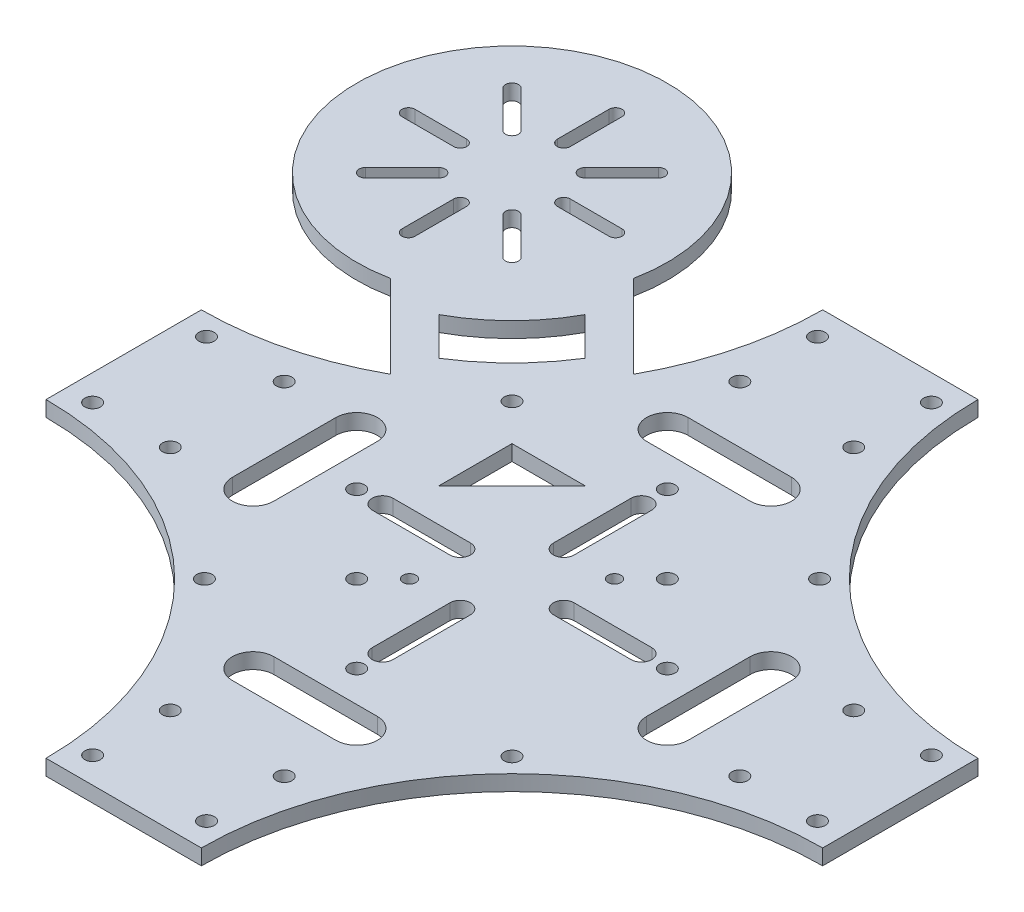
SolidWorks part; units mm, degrees
ref_plane "前视基准面" through (0, 0, 0) normal (0, 0, 1) x (1, 0, 0)
ref_plane "上视基准面" through (0, 0, 0) normal (0, 1, 0) x (1, 0, 0)
ref_plane "右视基准面" through (0, 0, 0) normal (1, 0, 0) x (0, 0, -1)
sketch "草图1" plane through (0, 0, 0) normal (0, 1, 0) x (1, 0, 0)
  line L0 (0, 0) -> (0, 75)
  line L1 (0, 0) -> (75, 0)
  line L2 (0, 0) -> (0, -75)
  line L3 (0, 0) -> (-75, 0)
  line L4 (0, 75) -> (15, 75)
  line L5 (0, 75) -> (-15, 75)
  line L6 (75, 0) -> (75, 15)
  line L7 (75, 0) -> (75, -15)
  line L8 (0, -75) -> (15, -75)
  line L9 (0, -75) -> (-15, -75)
  line L10 (-75, 0) -> (-75, -15)
  line L11 (-75, 0) -> (-75, 15)
  line L12 (75, 0) -> (70, 0)
  arc A0 (-75, 15) -> (-15, 75) centre (-75, 75) ccw
  arc A1 (15, 75) -> (75, 15) centre (75, 75) ccw
  arc A2 (75, -15) -> (15, -75) centre (75, -75) ccw
  arc A3 (-15, -75) -> (-75, -15) centre (-75, -75) ccw
  circle A4 centre (-11, 70) radius 1.25
  circle A5 centre (11, 70) radius 1.25
  circle A6 centre (70, -11) radius 1.25
  circle A7 centre (70, 11) radius 1.25
  circle A8 centre (-11, -70) radius 1.25
  circle A9 centre (11, -70) radius 1.25
  circle A10 centre (-70, 11) radius 1.25
  circle A11 centre (-70, -11) radius 1.25
  point P9 (0, 0)
  point P21 (0, 0)
  point P32 (0, 0)
  point P35 (0, 0)
  point P44 (0, 0)
  dimension "D1" = 4
extrude "凸台-拉伸1" add sketch "草图1" along normal blind 3 contours A2 L7 L1 L2 L8 A9 A6 | A3 L9 L2 L3 L10 A11 A8 | A0 L11 L3 L0 L5 A4 A10 | A1 L4 L0 L1 L6 A7 A5
sketch "草图2" plane through (0, 0, 0) normal (0, -1, 0) x (1, 0, 0)
  line L0 (0, 0) -> (-32.5736, -32.5736)
  line L1 (0, 0) -> (32.5736, -32.5736)
  line L2 (-31.4663, 0.3536) -> (-0.3536, 31.4663)
  line L3 (31.4663, -0.3536) -> (-0.3536, 31.4663)
  line L4 (0.3536, -31.4663) -> (31.4663, -0.3536)
  line L5 (0.3536, -31.4663) -> (-31.4663, 0.3536)
  arc A0 (-15, -75) -> (-75, -15) centre (-75, -75) ccw construction
  circle A2 centre (0.3536, -31.4663) radius 1.5
  circle A3 centre (31.4663, -0.3536) radius 1.5
  circle A4 centre (-0.3536, 31.4663) radius 1.5
  circle A5 centre (-31.4663, 0.3536) radius 1.5
  point P12 (-15.5563, -15.5563)
  point P16 (-15.9099, 15.9099)
  point P17 (15.9099, -15.9099)
extrude "切除-拉伸1" cut sketch "草图2" against normal blind 3 contours A3 | A2 | A5 | A4
sketch "草图3" plane through (0, 3, 0) normal (0, 1, 0) x (1, 0, 0)
  line L0 (0.3536, 31.4663) -> (-31.4663, -0.3536)
  line L1 (-15.5563, 15.5563) -> (-22.6274, 22.6274)
  line L2 (-15.5563, 15.5563) -> (-12.0208, 19.0919)
  line L3 (-15.5563, 15.5563) -> (-19.0919, 12.0208)
  line L4 (-19.0919, 12.0208) -> (-22.6274, 22.6274)
  line L5 (-12.0208, 19.0919) -> (-22.6274, 22.6274)
extrude "切除-拉伸2" cut sketch "草图3" against normal blind 3 contours L0 L5 L1 | L4 L0 L1
sketch "草图4" plane through (0, 3, 0) normal (0, 1, 0) x (1, 0, 0)
  line L0 (31.4663, 0.3536) -> (-0.3536, -31.4663)
  line L1 (0, 0) -> (21.2132, -21.2132)
  line L2 (28.2843, -14.1421) -> (14.1421, -28.2843)
  line L3 (14.1421, -28.2843) -> (28.2843, -14.1421) construction
  line L4 (8.4817, -22.6239) -> (22.6239, -8.4817)
  line L5 (19.8025, -33.9447) -> (33.9447, -19.8025)
  arc A0 (8.4817, -22.6239) -> (19.8025, -33.9447) centre (14.1421, -28.2843) ccw
  arc A1 (33.9447, -19.8025) -> (22.6239, -8.4817) centre (28.2843, -14.1421) ccw
  point P9 (21.2132, -21.2132)
extrude "切除-拉伸3" cut sketch "草图4" against normal blind 3
sketch "草图5" plane through (0, 3, 0) normal (0, 1, 0) x (1, 0, 0)
  line L0 (-12.0208, 19.0919) -> (-8.4853, 22.6274)
  line L1 (-8.4853, 22.6274) -> (-22.6274, 22.6274)
  line L2 (-19.0919, 12.0208) -> (-22.6274, 8.4853)
  line L3 (-22.6274, 8.4853) -> (-22.6274, 22.6274)
  line L4 (-12.0208, 19.0919) -> (-22.6274, 22.6274)
  line M28 (-19.0919, 12.0208) -> (-22.6274, 22.6274)
extrude "切除-拉伸4" cut sketch "草图5" against normal blind 10 contours L3 L2 M28 | L4 L0 L1
sketch "草图6" plane through (0, 3, 0) normal (0, 1, 0) x (1, 0, 0)
  line L0 (0, 0) -> (-28.2843, -28.2843)
  line L1 (-28.2843, -28.2843) -> (-35.3553, -21.2132)
  line L2 (0, 0) -> (-22.6274, 22.6274)
  circle A0 centre (-35.3553, -21.2132) radius 1.5
  circle A1 centre (-21.2132, -35.3553) radius 1.5
  circle A2 centre (35.3553, 21.2132) radius 1.5
  circle A3 centre (21.2132, 35.3553) radius 1.5
extrude "切除-拉伸5" cut sketch "草图6" against normal blind 10 contours A1 | A0 | A2 | A3
sketch "草图7" plane through (0, 3, 0) normal (0, 1, 0) x (1, 0, 0)
  circle A0 centre (-29.6985, 29.6985) radius 1.5
  circle A1 centre (29.6985, 29.6985) radius 1.5
  circle A2 centre (29.6985, -29.6985) radius 1.5
  circle A3 centre (-29.6985, -29.6985) radius 1.5
  point P11 (0, 0)
  dimension "D1" = 4
extrude "切除-拉伸8" cut sketch "草图7" against normal blind 10
sketch "草图8" plane through (0, 3, 0) normal (0, 1, 0) x (1, 0, 0)
  circle A0 centre (-11, 55) radius 1.5
  circle A1 centre (11, 55) radius 1.5
  circle A2 centre (55, 11) radius 1.5
  circle A3 centre (55, -11) radius 1.5
  circle A4 centre (11, -55) radius 1.5
  circle A5 centre (-11, -55) radius 1.5
  circle A6 centre (-55, -11) radius 1.5
  circle A7 centre (-55, 11) radius 1.5
  point P21 (0, 0)
  dimension "D1" = 4
extrude "切除-拉伸9" cut sketch "草图8" against normal blind 10
sketch "草图9" plane through (0, 3, 0) normal (0, 1, 0) x (1, 0, 0)
  circle A0 centre (0, 0) radius 15
extrude "切除-拉伸10" cut sketch "草图9" against normal blind 10
sketch "草图11" plane through (0, 3, 0) normal (0, 1, 0) x (1, 0, 0)
  circle A0 centre (-35.3553, -21.2132) radius 1.5
  circle A2 centre (35.3553, 21.2132) radius 1.5
  circle A3 centre (21.2132, 35.3553) radius 1.5
  circle A4 centre (0.3536, 31.4663) radius 1.5
  circle A5 centre (31.4663, 0.3536) radius 1.5
  circle A6 centre (-0.3536, -31.4663) radius 1.5
  circle A7 centre (-31.4663, -0.3536) radius 1.5
  circle A8 centre (-21.2132, -35.3553) radius 1.5
extrude "凸台-拉伸3" add sketch "草图11" against normal blind 3
sketch "草图12" plane through (0, 3, 0) normal (0, 1, 0) x (1, 0, 0)
  line L0 (0, 0) -> (-40, 0)
  line L1 (-40, 0) -> (-40, 10)
  line L2 (-40, 0) -> (-40, -10)
  line L3 (-40, -10) -> (-40, 10) construction
  line L4 (-44, -10) -> (-44, 10)
  line L5 (-36, -10) -> (-36, 10)
  line L6 (-10, 40) -> (10, 40) construction
  line L7 (-10, 44) -> (10, 44)
  line L8 (-10, 36) -> (10, 36)
  line L9 (40, 10) -> (40, -10) construction
  line L10 (44, 10) -> (44, -10)
  line L11 (36, 10) -> (36, -10)
  line L12 (10, -40) -> (-10, -40) construction
  line L13 (10, -44) -> (-10, -44)
  line L14 (10, -36) -> (-10, -36)
  arc A0 (-44, -10) -> (-36, -10) centre (-40, -10) ccw
  arc A1 (-36, 10) -> (-44, 10) centre (-40, 10) ccw
  arc A2 (-10, 44) -> (-10, 36) centre (-10, 40) ccw
  arc A3 (10, 36) -> (10, 44) centre (10, 40) ccw
  arc A4 (44, 10) -> (36, 10) centre (40, 10) ccw
  arc A5 (36, -10) -> (44, -10) centre (40, -10) ccw
  arc A6 (10, -44) -> (10, -36) centre (10, -40) ccw
  arc A7 (-10, -36) -> (-10, -44) centre (-10, -40) ccw
  point P3 (-40, 0)
  point P13 (0, 40)
  point P20 (40, 0)
  point P27 (0, -40)
  point P34 (0, 0)
  dimension "D1" = 4
extrude "切除-拉伸12" cut sketch "草图12" against normal blind 3
sketch "草图14" plane through (0, 3, 0) normal (0, 1, 0) x (1, 0, 0)
  line L0 (22.8277, -8.285) -> (8.285, -22.8277) construction
  line L1 (19.8025, -33.9447) -> (33.9447, -19.8025) construction
  line L2 (8.285, -22.8277) -> (22.8277, -8.285)
  line L3 (22.8277, -8.285) -> (19.8025, -33.9447)
  line L4 (19.8025, -33.9447) -> (33.9447, -19.8025)
  arc A0 (8.285, -22.8277) -> (19.8025, -33.9447) centre (14.1421, -28.2843) ccw
  arc A1 (8.285, -22.8277) -> (19.8025, -33.9447) centre (14.1421, -28.2843) ccw construction
  arc A2 (33.9447, -19.8025) -> (22.8277, -8.285) centre (28.2843, -14.1421) ccw construction
  arc A3 (22.8277, -8.285) -> (32.1857, -7.1522) centre (28.2843, -14.1421) ccw
  circle A4 centre (28.2843, -14.1421) radius 8.005
extrude "凸台-拉伸4" add sketch "草图14" against normal blind 3 contours A3 A4 L3 | L2 A3 L3 | A3 L2 A0 L3 | A3 L3 L4
sketch "草图15" plane through (0, 3, 0) normal (0, 1, 0) x (1, 0, 0)
  circle A0 centre (0, 0) radius 15
extrude "凸台-拉伸5" add sketch "草图15" against normal blind 3
sketch "草图17" plane through (0, 3, 0) normal (0, 1, 0) x (1, 0, 0)
  line L0 (0, 0) -> (0, -20)
  line L1 (0, -20) -> (0, -10) construction
  line L2 (-2, -20) -> (-2, -10)
  line L3 (2, -20) -> (2, -10)
  line L4 (-20, 0) -> (-10, 0) construction
  line L5 (-20, 2) -> (-10, 2)
  line L6 (-20, -2) -> (-10, -2)
  line L7 (0, 20) -> (0, 10) construction
  line L8 (2, 20) -> (2, 10)
  line L9 (-2, 20) -> (-2, 10)
  line L10 (20, 0) -> (10, 0) construction
  line L11 (20, -2) -> (10, -2)
  line L12 (20, 2) -> (10, 2)
  arc A0 (-2, -20) -> (2, -20) centre (0, -20) ccw
  arc A1 (2, -10) -> (-2, -10) centre (0, -10) ccw
  arc A2 (-20, 2) -> (-20, -2) centre (-20, 0) ccw
  arc A3 (-10, -2) -> (-10, 2) centre (-10, 0) ccw
  arc A4 (2, 20) -> (-2, 20) centre (0, 20) ccw
  arc A5 (-2, 10) -> (2, 10) centre (0, 10) ccw
  arc A6 (20, -2) -> (20, 2) centre (20, 0) ccw
  arc A7 (10, 2) -> (10, -2) centre (10, 0) ccw
  point P3 (0, -15)
  point P13 (-15, 0)
  point P20 (0, 15)
  point P27 (15, 0)
  point P33 (0, 0)
  dimension "D1" = 4
extrude "切除-拉伸13" cut sketch "草图17" against normal blind 3 contours L8 A5 L9 A4 | L12 A7 L11 A6 | L3 A1 L2 A0 | L5 A3 L6 A2
sketch "草图18" plane through (0, 3, 0) normal (0, 1, 0) x (1, 0, 0)
  line L0 (0, 0) -> (-32.5736, 32.5736)
  line L1 (-32.5736, 32.5736) -> (-46.7157, 46.7157)
  line L2 (-50.2513, 50.2513) -> (-61.9773, 38.5252)
  line L3 (-46.7157, 46.7157) -> (-50.2513, 50.2513)
  line L4 (-61.9773, 38.5252) -> (-38.5252, 61.9773)
  line L5 (-38.5252, 61.9773) -> (-22.5002, 45.9523)
  line L6 (-61.9773, 38.5252) -> (-45.9523, 22.5002)
  arc A0 (-75, 15) -> (-15, 75) centre (-75, 75) ccw construction
  circle A1 centre (-67.9289, 67.9289) radius 30
  circle A2 centre (-75, 75) radius 60
extrude "凸台-拉伸7" add sketch "草图18" against normal blind 3 contours L4 A1 L2 | L2 A1 L3 | L3 A1 L4 | L6 A2 L1 A1 | L1 A2 L5 A1
sketch "草图19" plane through (0, 3, 0) normal (0, 1, 0) x (1, 0, 0)
  line L0 (-61.9773, 38.5252) -> (-38.5252, 61.9773)
  line L1 (-50.2513, 50.2513) -> (-36.1091, 36.1091)
  line L2 (-36.1091, 36.1091) -> (-43.1802, 29.0381)
  line L3 (-36.1091, 36.1091) -> (-29.0381, 43.1802)
  line L4 (-29.0381, 43.1802) -> (-37.1408, 51.2829)
  line L5 (-37.1408, 51.2829) -> (-51.2829, 37.1408)
  line L6 (-51.2829, 37.1408) -> (-43.1802, 29.0381)
  circle A1 centre (-67.9289, 67.9289) radius 35
  circle A2 centre (-67.9289, 67.9289) radius 45
extrude "切除-拉伸14" cut sketch "草图19" against normal blind 3 contours L1 A2 L4 A1 | L6 A2 L1 A1
sketch "草图21" plane through (0, 3, 0) normal (0, 1, 0) x (1, 0, 0)
  line L0 (-61.9773, 38.5252) -> (-38.5252, 61.9773)
  line L1 (-67.9289, 67.9289) -> (-53.7868, 53.7868)
  line L2 (-82.0711, 82.0711) -> (-75, 75)
  line L3 (-67.9289, 67.9289) -> (-82.0711, 82.0711)
  line L4 (-53.7868, 53.7868) -> (-60.8579, 60.8579)
  line L5 (-82.0711, 82.0711) -> (-75, 75) construction
  line L6 (-81.1872, 82.955) -> (-74.1161, 75.8839)
  line L7 (-82.955, 81.1872) -> (-75.8839, 74.1161)
  line L8 (-60.8579, 60.8579) -> (-53.7868, 53.7868) construction
  line L9 (-59.974, 61.7417) -> (-52.9029, 54.6707)
  line L10 (-61.7417, 59.974) -> (-54.6707, 52.9029)
  arc A0 (-81.1872, 82.955) -> (-82.955, 81.1872) centre (-82.0711, 82.0711) ccw
  arc A1 (-75.8839, 74.1161) -> (-74.1161, 75.8839) centre (-75, 75) ccw
  arc A2 (-59.974, 61.7417) -> (-61.7417, 59.974) centre (-60.8579, 60.8579) ccw
  arc A3 (-54.6707, 52.9029) -> (-52.9029, 54.6707) centre (-53.7868, 53.7868) ccw
  point P2 (-78.5355, 78.5355)
  point P15 (-57.3223, 57.3223)
extrude "切除-拉伸15" cut sketch "草图21" against normal blind 3
pattern_circular "阵列(圆周)1" count 8 over 360 about axis through (-67.9289, 0, -67.9289) along (0, 1, 0) of "切除-拉伸15"
sketch "草图22" plane through (0, 3, 0) normal (0, 1, 0) x (1, 0, 0)
  line L0 (0, 0) -> (9.8995, 9.8995)
  line L1 (0, 0) -> (-9.8995, -9.8995)
  circle A0 centre (9.8995, 9.8995) radius 1.25
  circle A1 centre (-9.8995, -9.8995) radius 1.25
extrude "切除-拉伸17" cut sketch "草图22" against normal blind 3 contours A0 | A1
sketch "草图23" plane through (0, 3, 0) normal (0, 1, 0) x (1, 0, 0)
  circle A0 centre (0, 30) radius 1.5
  circle A1 centre (30, 0) radius 1.5
  circle A2 centre (0, -30) radius 1.5
  circle A3 centre (-30, 0) radius 1.5
  point P13 (0, 0)
  dimension "D1" = 4
extrude "切除-拉伸18" cut sketch "草图23" against normal blind 10
sketch "草图24" plane through (0, 3, 0) normal (0, 1, 0) x (1, 0, 0)
  circle A0 centre (-15, -15) radius 1.5
  circle A1 centre (15, 15) radius 1.5
extrude "切除-拉伸19" cut sketch "草图24" against normal blind 10
sketch "草图25" plane through (0, 3, 0) normal (0, 1, 0) x (1, 0, 0)
  line L0 (0, 10) -> (0, 25)
  line L1 (0, 10) -> (0, 25) construction
  line L2 (-2, 10) -> (-2, 25)
  line L3 (2, 10) -> (2, 25)
  line L4 (10, 0) -> (25, 0) construction
  line L5 (10, 2) -> (25, 2)
  line L6 (10, -2) -> (25, -2)
  line L7 (0, -10) -> (0, -25) construction
  line L8 (2, -10) -> (2, -25)
  line L9 (-2, -10) -> (-2, -25)
  line L10 (-10, 0) -> (-25, 0) construction
  line L11 (-10, -2) -> (-25, -2)
  line L12 (-10, 2) -> (-25, 2)
  arc A0 (-2, 10) -> (2, 10) centre (0, 10) ccw
  arc A1 (2, 25) -> (-2, 25) centre (0, 25) ccw
  arc A3 (10, 2) -> (10, -2) centre (10, 0) ccw
  arc A4 (25, -2) -> (25, 2) centre (25, 0) ccw
  arc A5 (2, -10) -> (-2, -10) centre (0, -10) ccw
  arc A6 (-2, -25) -> (2, -25) centre (0, -25) ccw
  arc A7 (-10, -2) -> (-10, 2) centre (-10, 0) ccw
  arc A8 (-25, 2) -> (-25, -2) centre (-25, 0) ccw
  point P4 (0, 17.5)
  point P14 (17.5, 0)
  point P21 (0, -17.5)
  point P28 (-17.5, 0)
  point P33 (0, 0)
  dimension "D1" = 4
extrude "切除-拉伸20" cut sketch "草图25" against normal blind 10 contours L12 A8 L11 A7 | L5 A4 L6 A3 | A1 L2 A0 L3 | L8 A6 L9 A5
sketch "草图26" plane through (0, 3, 0) normal (0, 1, 0) x (1, 0, 0)
  circle A0 centre (11, 70) radius 1.5
  circle A1 centre (-11, 70) radius 1.5
  circle A2 centre (70, 11) radius 1.5
  circle A3 centre (70, -11) radius 1.5
  circle A4 centre (11, -70) radius 1.5
  circle A5 centre (-11, -70) radius 1.5
  circle A6 centre (-70, -11) radius 1.5
  circle A7 centre (-70, 11) radius 1.5
  point P21 (0, 0)
  dimension "D1" = 4
extrude "切除-拉伸21" cut sketch "草图26" against normal blind 66
